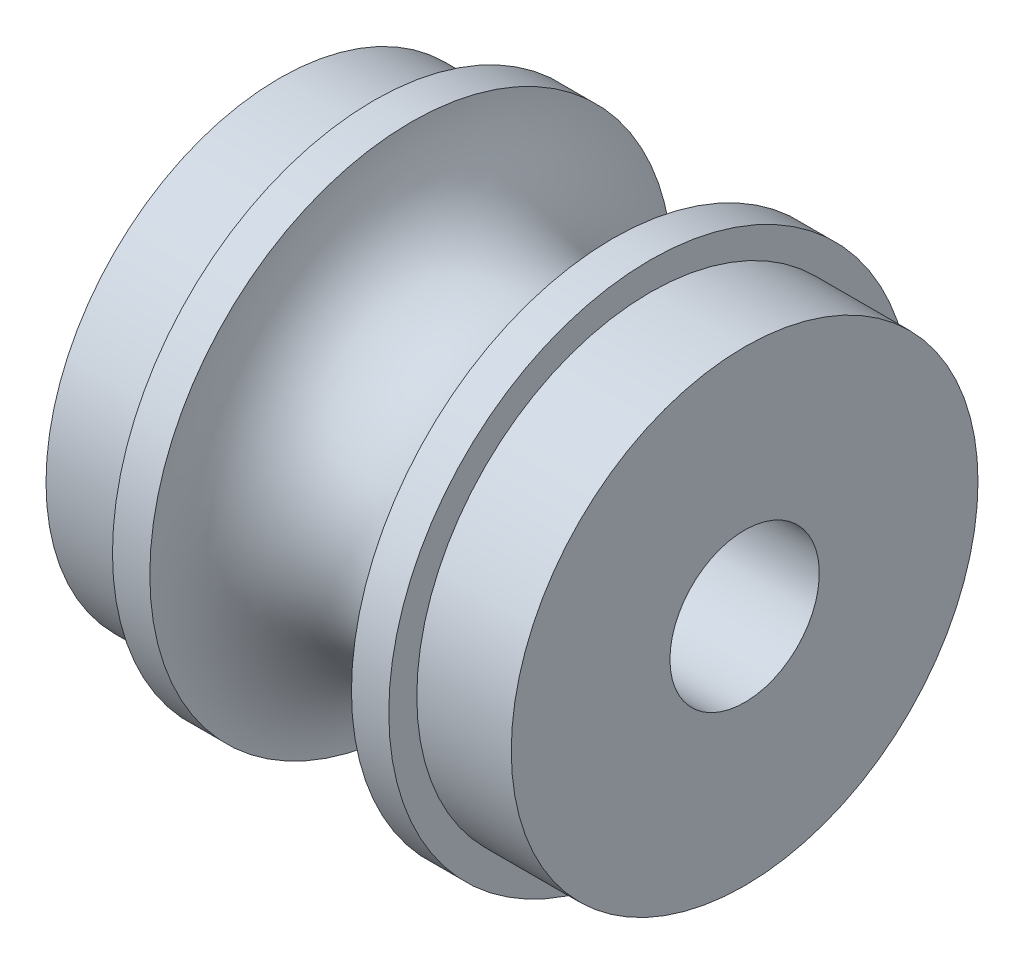
SolidWorks part; units mm, degrees
ref_plane "Front Plane" through (0, 0, 0) normal (0, 0, 1) x (1, 0, 0)
ref_plane "Top Plane" through (0, 0, 0) normal (0, 1, 0) x (1, 0, 0)
ref_plane "Right Plane" through (0, 0, 0) normal (1, 0, 0) x (0, 0, -1)
sketch "Sketch1" plane through (0, 0, 0) normal (0, 0, 1) x (1, 0, 0)
  line L0 (0, 8.89) -> (0, 0)
  line L1 (0, 0) -> (6.858, 0)
  line L2 (6.858, 0) -> (6.858, 8.89)
  line L4 (0, 0) -> (-1.27, 0)
  line L5 (0, 0) -> (0, 8.89)
  line L6 (0, 8.89) -> (-1.27, 8.89)
  line L7 (-1.27, 0) -> (-1.27, 8.89)
  line L8 (6.858, 8.89) -> (8.128, 8.89)
  line L9 (6.858, 8.89) -> (6.858, 0)
  line L10 (6.858, 0) -> (8.128, 0)
  line L11 (8.128, 8.89) -> (8.128, 0)
  arc A0 (0, 8.89) -> (6.858, 8.89) centre (3.429, 8.89) ccw
  point P8 (3.429, 0)
  dimension "D1" = 6.858
  dimension "D2" = 8.89
  dimension "D3" = 1.27
revolve "Revolve1" add sketch "Sketch1" angle 360 about L1
sketch "Sketch2" plane through (8.128, 0, 0) normal (1, 0, 0) x (0, 0, -1)
  circle A0 centre (0, 0) radius 7.9375
  dimension "D1" = 15.875
extrude "Boss-Extrude1" add sketch "Sketch2" along normal blind 3.2131
sketch "Sketch3" plane through (-1.27, 0, 0) normal (-1, 0, 0) x (0, 0, 1)
  circle A0 centre (0, 0) radius 7.9375
  circle A1 centre (0, 0) radius 7.9375 construction
extrude "Boss-Extrude2" add sketch "Sketch3" along normal blind 3.2131
sketch "Sketch4" plane through (-4.4831, 0, 0) normal (-1, 0, 0) x (0, 0, 1)
  circle A0 centre (0, 0) radius 2.54
  dimension "D1" = 5.08
extrude "Cut-Extrude1" cut sketch "Sketch4" against normal through all
